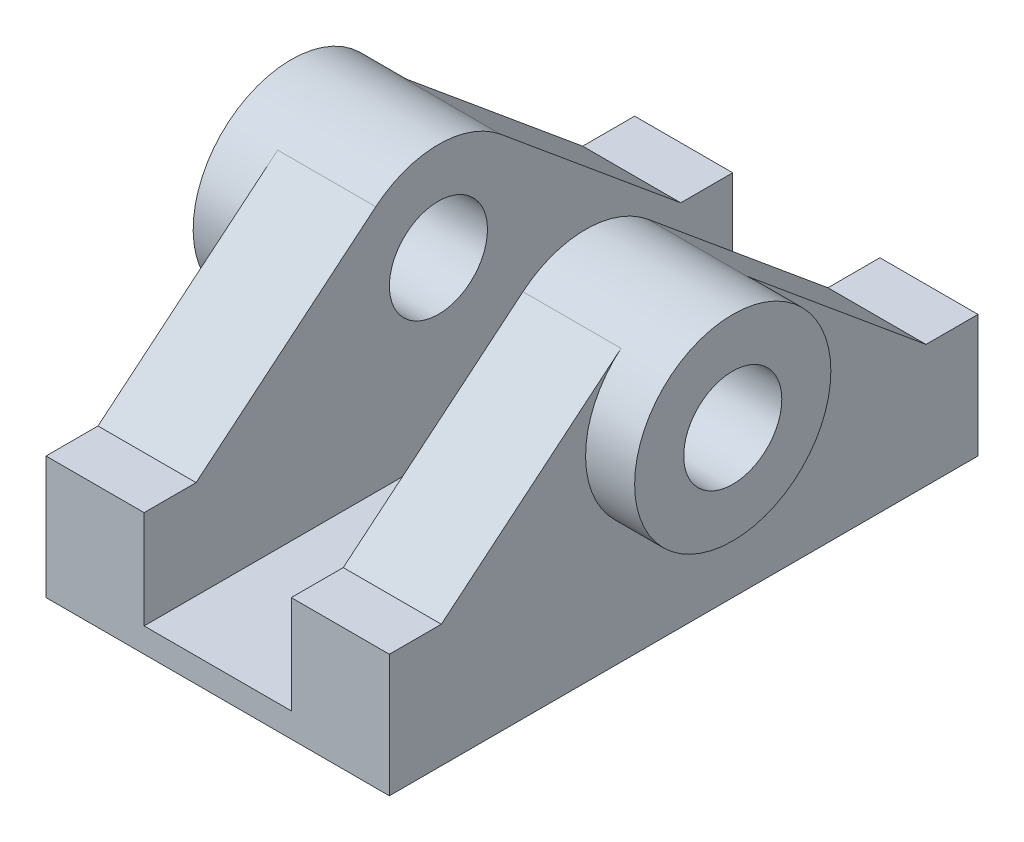
SolidWorks part; units mm, degrees
ref_plane "Front Plane" through (0, 0, 0) normal (0, 0, 1) x (1, 0, 0)
ref_plane "Top Plane" through (0, 0, 0) normal (0, 1, 0) x (1, 0, 0)
ref_plane "Right Plane" through (0, 0, 0) normal (1, 0, 0) x (0, 0, -1)
sketch "Sketch1" plane through (0, 0, 0) normal (0, 1, 0) x (1, 0, 0)
  line L5 (-35, -60) -> (35, -60)
  line L6 (-35, -60) -> (-35, 60)
  line L7 (-35, 60) -> (35, 60)
  line L8 (35, -60) -> (35, 60)
  line L9 (-35, -60) -> (35, 60) construction
  line L10 (-35, 60) -> (35, -60) construction
  point P0 (0, 0)
  dimension "D1" = 70
  dimension "D2" = 120
extrude "Boss-Extrude1" add sketch "Sketch1" along normal blind 25
sketch "Sketch2" plane through (0, 25, 0) normal (0, 1, 0) x (1, 0, 0)
  line L0 (35, 60) -> (-35, 60) construction
  line L1 (-15, -60) -> (15, -60)
  line L2 (-15, -60) -> (-15, 60)
  line L3 (-15, 60) -> (15, 60)
  line L4 (15, -60) -> (15, 60)
  line L5 (-15, -60) -> (15, 60) construction
  line L6 (-15, 60) -> (15, -60) construction
  point P0 (0, 0)
  dimension "D1" = 30
extrude "Cut-Extrude1" cut sketch "Sketch2" against normal blind 20
ref_plane "Plane1" through (45, 0, 0) normal (1, 0, 0) x (0, 0, -1)
sketch "Sketch4" plane through (45, 0, 0) normal (1, 0, 0) x (0, 0, -1)
  circle A0 centre (0, 40) radius 20
  circle A1 centre (0, 40) radius 10
  dimension "D1" = 40
  dimension "D2" = 20
  dimension "D3" = 40
extrude "Boss-Extrude2" add sketch "Sketch4" against normal blind 30
mirror "Mirror1" about plane through (0, 0, 0) normal (1, 0, 0) of "Boss-Extrude2"
sketch "Sketch5" plane through (-35, 0, 0) normal (-1, 0, 0) x (0, 0, 1)
  line L0 (-12.7701, 55.3924) -> (-49.4033, 25)
  line L2 (-60, 25) -> (-13.2288, 25) construction
  line L4 (0, -33) -> (0, 33) construction
  line L5 (12.7701, 55.3924) -> (49.4033, 25)
  line L6 (-49.4033, 25) -> (-13.2288, 25)
  circle A1 centre (0, 40) radius 20 construction
  circle A4 centre (0, 40) radius 20
  line M4 (-13.2288, 25) -> (-60, 25)
  line M8 (60, 25) -> (13.2288, 25)
extrude "Boss-Extrude3" add sketch "Sketch5" against normal blind 20 contours A4 L0 M4 | A4 L5 M8
mirror "Mirror2" about plane through (0, 0, 0) normal (1, 0, 0) of "Boss-Extrude3"
